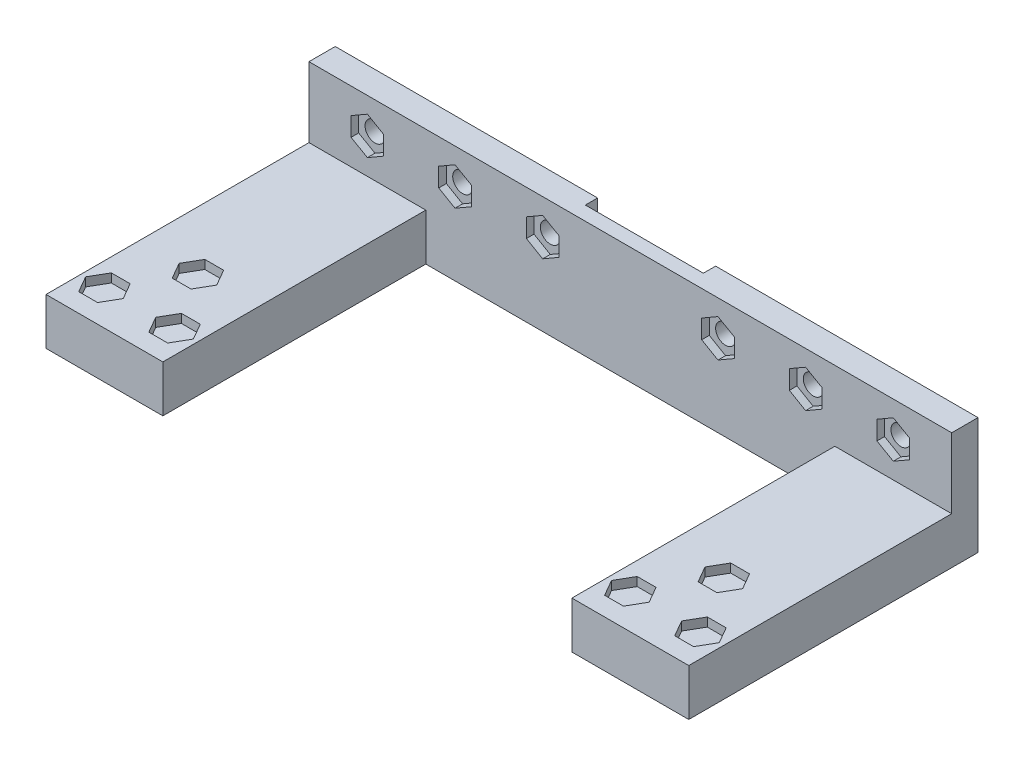
SolidWorks part; units mm, degrees
ref_plane "前视基准面" through (0, 0, 0) normal (0, 0, 1) x (1, 0, 0)
ref_plane "上视基准面" through (0, 0, 0) normal (0, 1, 0) x (1, 0, 0)
ref_plane "右视基准面" through (0, 0, 0) normal (1, 0, 0) x (0, 0, -1)
sketch "草图1" plane through (0, 0, 0) normal (0, 0, 1) x (1, 0, 0)
  line L6 (-55, 0) -> (55, 0)
  line L11 (55, 0) -> (55, 20)
  line L12 (55, 20) -> (-55, 20)
  line L13 (-55, 20) -> (-55, 0)
  line L14 (-45, 14) -> (45, 14) construction
  line L15 (0, 14) -> (0, 0) construction
  circle A6 centre (-45, 14) radius 1.7
  circle A7 centre (-30, 14) radius 1.7
  circle A8 centre (-15, 14) radius 1.7
  circle A9 centre (15, 14) radius 1.7
  circle A10 centre (30, 14) radius 1.7
  circle A11 centre (45, 14) radius 1.7
  dimension "D1" = 110
  dimension "D2" = 3.4
  dimension "D3" = 90
  dimension "D4" = 60
  dimension "D5" = 30
  dimension "D6" = 20
  dimension "D7" = 6
extrude "凸台-拉伸1" add sketch "草图1" along normal blind 4.5
sketch "草图2" plane through (0, 0, 4.5) normal (0, 0, 1) x (1, 0, 0)
  line L0 (0, 0) -> (0, 12.4325) construction
  line L1 (-55, 0) -> (-35, 0)
  line L2 (-55, 0) -> (-55, 8)
  line L3 (-55, 8) -> (-35, 8)
  line L4 (-35, 0) -> (-35, 8)
  line L5 (55, 0) -> (35, 0)
  line L6 (55, 0) -> (55, 8)
  line L7 (55, 8) -> (35, 8)
  line L8 (35, 0) -> (35, 8)
  dimension "D1" = 8
  dimension "D2" = 20
extrude "凸台-拉伸2" add sketch "草图2" along normal blind 45
sketch "草图3" plane through (0, 0, 4.5) normal (0, 0, 1) x (1, 0, 0)
  line L1 (-45, 17.22) -> (-47.7886, 15.61)
  line L2 (-47.7886, 15.61) -> (-47.7886, 12.39)
  line L3 (-47.7886, 12.39) -> (-45, 10.78)
  line L4 (-45, 10.78) -> (-42.2114, 12.39)
  line L5 (-42.2114, 12.39) -> (-42.2114, 15.61)
  line L6 (-42.2114, 15.61) -> (-45, 17.22)
  line L7 (-30, 17.22) -> (-32.7886, 15.61)
  line L8 (-32.7886, 15.61) -> (-32.7886, 12.39)
  line L9 (-32.7886, 12.39) -> (-30, 10.78)
  line L10 (-30, 10.78) -> (-27.2114, 12.39)
  line L11 (-27.2114, 12.39) -> (-27.2114, 15.61)
  line L12 (-27.2114, 15.61) -> (-30, 17.22)
  line L13 (-15, 17.22) -> (-17.7886, 15.61)
  line L14 (-17.7886, 15.61) -> (-17.7886, 12.39)
  line L15 (-17.7886, 12.39) -> (-15, 10.78)
  line L16 (-15, 10.78) -> (-12.2114, 12.39)
  line L17 (-12.2114, 12.39) -> (-12.2114, 15.61)
  line L18 (-12.2114, 15.61) -> (-15, 17.22)
  line L19 (15, 17.22) -> (12.2114, 15.61)
  line L20 (12.2114, 15.61) -> (12.2114, 12.39)
  line L21 (12.2114, 12.39) -> (15, 10.78)
  line L22 (15, 10.78) -> (17.7886, 12.39)
  line L23 (17.7886, 12.39) -> (17.7886, 15.61)
  line L24 (17.7886, 15.61) -> (15, 17.22)
  line L25 (30, 17.22) -> (27.2114, 15.61)
  line L26 (27.2114, 15.61) -> (27.2114, 12.39)
  line L27 (27.2114, 12.39) -> (30, 10.78)
  line L28 (30, 10.78) -> (32.7886, 12.39)
  line L29 (32.7886, 12.39) -> (32.7886, 15.61)
  line L30 (32.7886, 15.61) -> (30, 17.22)
  line L31 (45, 17.22) -> (42.2114, 15.61)
  line L32 (42.2114, 15.61) -> (42.2114, 12.39)
  line L33 (42.2114, 12.39) -> (45, 10.78)
  line L34 (45, 10.78) -> (47.7886, 12.39)
  line L35 (47.7886, 12.39) -> (47.7886, 15.61)
  line L36 (47.7886, 15.61) -> (45, 17.22)
  circle A0 centre (-45, 14) radius 2.7886 construction
  circle A1 centre (-30, 14) radius 2.7886 construction
  circle A2 centre (-15, 14) radius 2.7886 construction
  circle A3 centre (15, 14) radius 2.7886 construction
  circle A4 centre (30, 14) radius 2.7886 construction
  circle A5 centre (45, 14) radius 2.7886 construction
  dimension "D1" = 3.22
extrude "切除-拉伸1" cut sketch "草图3" against normal blind 1.3
sketch "草图10" plane through (0, 0, 0) normal (0, -1, 0) x (1, 0, 0)
  line L0 (0, 0) -> (10.1, 0)
  line L1 (-55, 0) -> (55, 0) construction
  line L2 (10.1, 0) -> (10.1, 2.1)
  line L3 (10.1, 2.1) -> (-10.1, 2.1)
  line L4 (-10.1, 2.1) -> (-10.1, 0)
  line L5 (-10.1, 0) -> (0, 0)
  dimension "D1" = 10.1
  dimension "D2" = 10.1
  dimension "D3" = 2.1
extrude "切除-拉伸2" cut sketch "草图10" against normal blind 29
sketch "草图11" plane through (0, 0, 0) normal (0, -1, 0) x (1, 0, 0)
  circle A0 centre (-331.7687, -207.6416) radius 1.7
  circle A1 centre (-337.7687, -197.6416) radius 1.7
  circle A2 centre (-325.7687, -197.6416) radius 1.7
  circle A3 centre (-247.7687, -197.6416) radius 1.7
  circle A4 centre (-235.7687, -197.6416) radius 1.7
  circle A5 centre (-241.7687, -207.6416) radius 1.7
extrude "切除-拉伸3" cut sketch "草图11" against normal blind 167
sketch "草图12" plane through (0, 8, 0) normal (0, 1, 0) x (1, 0, 0)
  line L0 (0, 11.9163) -> (0, -63.3503) construction
  line L1 (-41.78, -33.5) -> (-43.39, -30.7114)
  line L2 (-43.39, -30.7114) -> (-46.61, -30.7114)
  line L3 (-46.61, -30.7114) -> (-48.22, -33.5)
  line L4 (-48.22, -33.5) -> (-46.61, -36.2886)
  line L5 (-46.61, -36.2886) -> (-43.39, -36.2886)
  line L6 (-43.39, -36.2886) -> (-41.78, -33.5)
  line L7 (-47.78, -43.5) -> (-49.39, -40.7114)
  line L8 (-49.39, -40.7114) -> (-52.61, -40.7114)
  line L9 (-52.61, -40.7114) -> (-54.22, -43.5)
  line L10 (-54.22, -43.5) -> (-52.61, -46.2886)
  line L11 (-52.61, -46.2886) -> (-49.39, -46.2886)
  line L12 (-49.39, -46.2886) -> (-47.78, -43.5)
  line L13 (-35.78, -43.5) -> (-37.39, -40.7114)
  line L14 (-37.39, -40.7114) -> (-40.61, -40.7114)
  line L15 (-40.61, -40.7114) -> (-42.22, -43.5)
  line L16 (-42.22, -43.5) -> (-40.61, -46.2886)
  line L17 (-40.61, -46.2886) -> (-37.39, -46.2886)
  line L18 (-37.39, -46.2886) -> (-35.78, -43.5)
  line L19 (37.39, -46.2886) -> (35.78, -43.5)
  line L20 (40.61, -46.2886) -> (37.39, -46.2886)
  line L21 (42.22, -43.5) -> (40.61, -46.2886)
  line L22 (40.61, -40.7114) -> (42.22, -43.5)
  line L23 (37.39, -40.7114) -> (40.61, -40.7114)
  line L24 (35.78, -43.5) -> (37.39, -40.7114)
  line L25 (49.39, -46.2886) -> (47.78, -43.5)
  line L26 (52.61, -46.2886) -> (49.39, -46.2886)
  line L27 (54.22, -43.5) -> (52.61, -46.2886)
  line L28 (52.61, -40.7114) -> (54.22, -43.5)
  line L29 (49.39, -40.7114) -> (52.61, -40.7114)
  line L30 (47.78, -43.5) -> (49.39, -40.7114)
  line L31 (43.39, -36.2886) -> (41.78, -33.5)
  line L32 (46.61, -36.2886) -> (43.39, -36.2886)
  line L33 (48.22, -33.5) -> (46.61, -36.2886)
  line L34 (46.61, -30.7114) -> (48.22, -33.5)
  line L35 (43.39, -30.7114) -> (46.61, -30.7114)
  line L36 (41.78, -33.5) -> (43.39, -30.7114)
  line L37 (-35, -49.5) -> (-55, -49.5) construction
  circle A0 centre (-45, -33.5) radius 2.7886 construction
  circle A1 centre (-51, -43.5) radius 2.7886 construction
  circle A2 centre (-39, -43.5) radius 2.7886 construction
  circle A3 centre (39, -43.5) radius 2.7886 construction
  circle A4 centre (51, -43.5) radius 2.7886 construction
  circle A5 centre (45, -33.5) radius 2.7886 construction
  dimension "D1" = 3.22
  dimension "D2" = 3.22
  dimension "D3" = 3.22
extrude "切除-拉伸4" cut sketch "草图12" against normal blind 1.5
